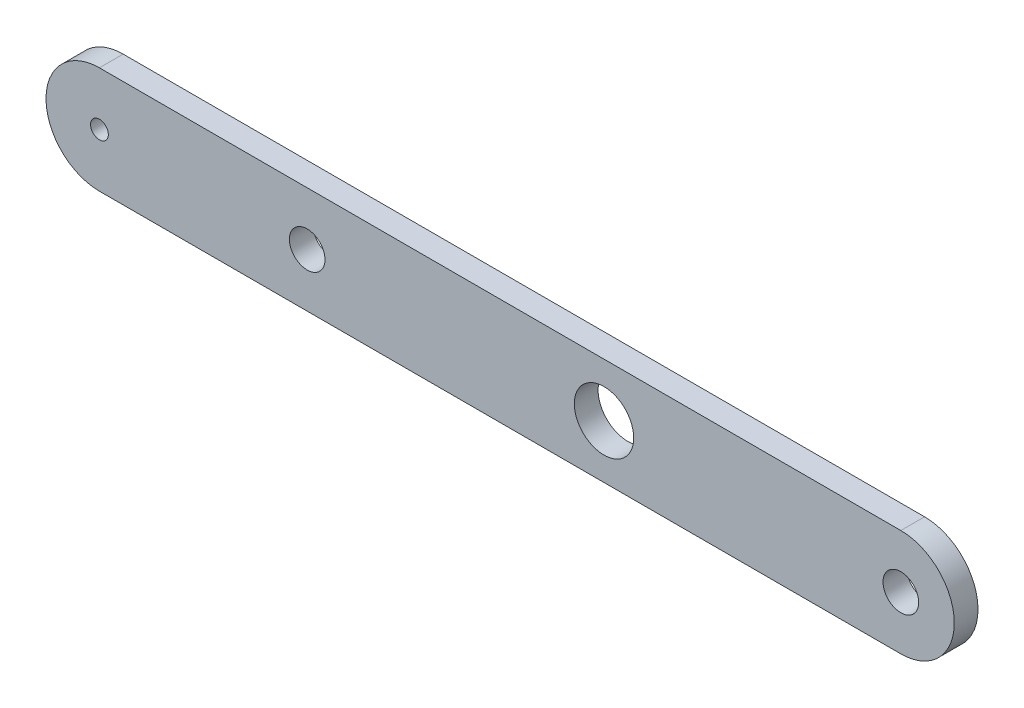
SolidWorks part; units mm, degrees
ref_plane "正面" through (0, 0, 0) normal (0, 0, 1) x (1, 0, 0)
ref_plane "平面" through (0, 0, 0) normal (0, 1, 0) x (1, 0, 0)
ref_plane "右側面" through (0, 0, 0) normal (1, 0, 0) x (0, 0, -1)
sketch "ｽｹｯﾁ1" plane through (0, 0, 0) normal (0, 0, 1) x (1, 0, 0)
  line L0 (-35, 0) -> (100, 0) construction
  line L1 (-35, 9) -> (100, 9)
  line L2 (-35, -9) -> (100, -9)
  arc A0 (-35, 9) -> (-35, -9) centre (-35, 0) ccw
  arc A1 (100, -9) -> (100, 9) centre (100, 0) ccw
  circle A2 centre (100, 0) radius 3
  circle A3 centre (0, 0) radius 3
  circle A4 centre (-35, 0) radius 1.5
  circle A5 centre (50, 0) radius 5
  point P3 (32.5, 0)
  dimension "D2" = 6
  dimension "D3" = 9
  dimension "D4" = 6
  dimension "D5" = 3
  dimension "D7" = 10
  dimension "D1" = 100
  dimension "D6" = 35
  dimension "D8" = 50
extrude "ﾎﾞｽ - 押し出し1" add sketch "ｽｹｯﾁ1" along normal blind 4
